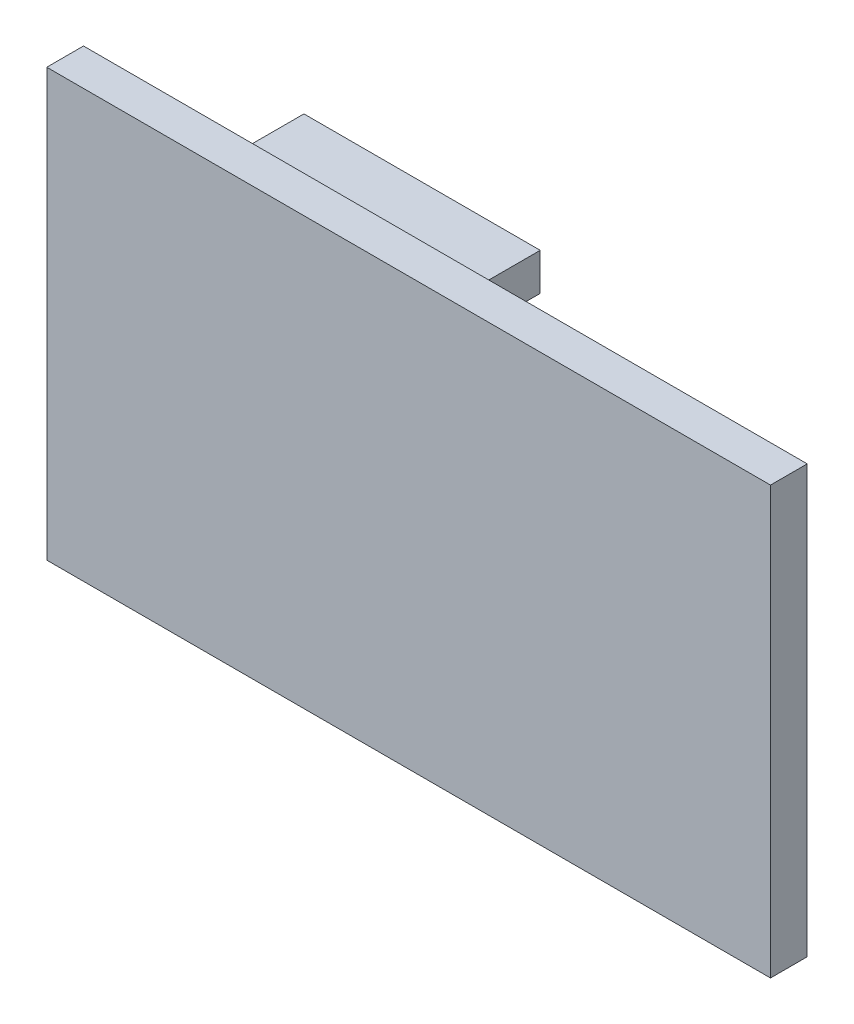
SolidWorks part; units mm, degrees
ref_plane "Front Plane" through (0, 0, 0) normal (0, 0, 1) x (1, 0, 0)
ref_plane "Top Plane" through (0, 0, 0) normal (0, 1, 0) x (1, 0, 0)
ref_plane "Right Plane" through (0, 0, 0) normal (1, 0, 0) x (0, 0, -1)
sketch "Sketch1" plane through (0, 0, 0) normal (0, 0, 1) x (1, 0, 0)
  line L1 (-49.25, 29.05) -> (49.25, 29.05)
  line L2 (-49.25, 29.05) -> (-49.25, -29.05)
  line L3 (-49.25, -29.05) -> (49.25, -29.05)
  line L4 (49.25, 29.05) -> (49.25, -29.05)
  line L5 (-49.25, 29.05) -> (49.25, -29.05) construction
  line L6 (-49.25, -29.05) -> (49.25, 29.05) construction
  point P0 (0, 0)
  dimension "D1" = 98.5
  dimension "D2" = 58.1
extrude "Boss-Extrude1" add sketch "Sketch1" along normal blind 5
sketch "Sketch2" plane through (0, 0, 0) normal (0, 0, -1) x (-1, 0, 0)
  line L0 (-49.25, 29.05) -> (49.25, 29.05) construction
  line L6 (-49.25, -29.05) -> (-49.25, 29.05) construction
  line L8 (49.25, 29.05) -> (49.25, -29.05) construction
  line L10 (-2.91, 26.05) -> (29.25, 26.05)
  line L11 (-2.91, 26.05) -> (-2.91, 20.97)
  line L12 (-2.91, 20.97) -> (29.25, 20.97)
  line L13 (29.25, 26.05) -> (29.25, 20.97)
  dimension "D4" = 5.08
  dimension "D5" = 20
  dimension "D6" = 46.34
  dimension "D7" = 3
extrude "Boss-Extrude2" add sketch "Sketch2" along normal blind 10
